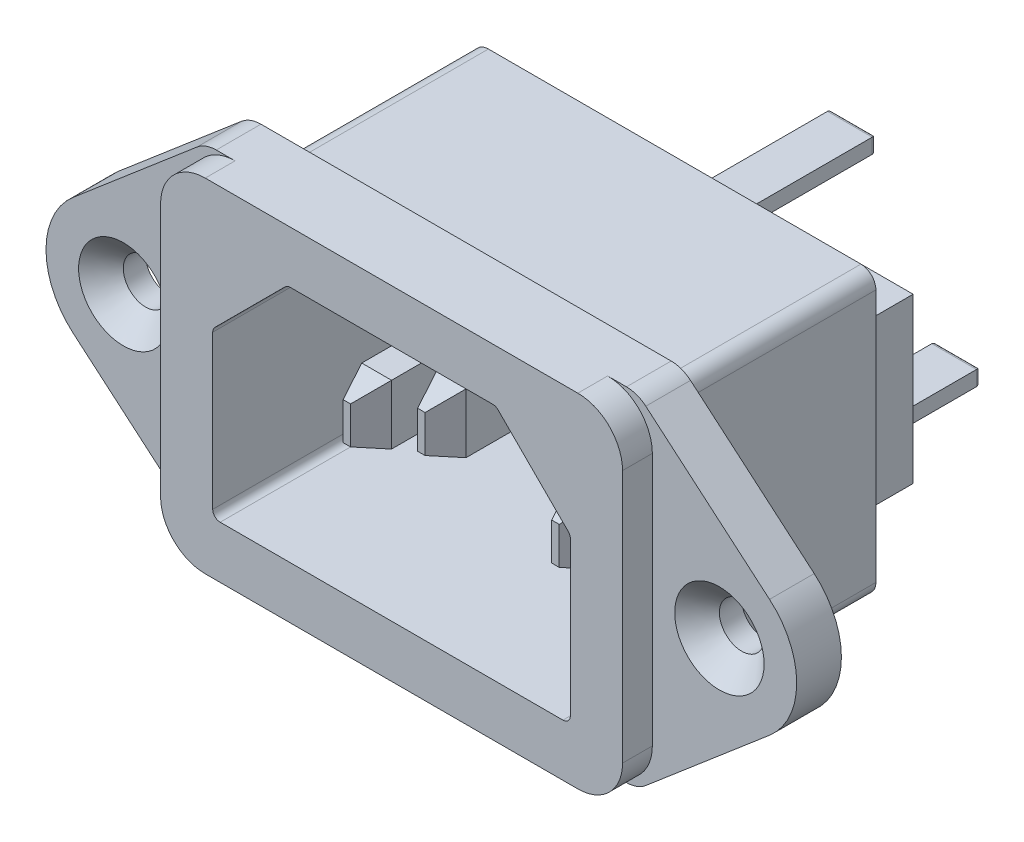
SolidWorks part; units mm, degrees
material "Gummi"
ref_plane "Ebene vorne" through (0, 0, 0) normal (0, 0, 1) x (1, 0, 0)
ref_plane "Ebene oben" through (0, 0, 0) normal (0, 1, 0) x (1, 0, 0)
ref_plane "Ebene rechts" through (0, 0, 0) normal (1, 0, 0) x (0, 0, -1)
sketch "Skizze1" plane through (0, 0, 0) normal (0, 0, 1) x (1, 0, 0)
  line L0 (28, 0) -> (-28, 0) construction
  line L1 (14.5, -11.5) -> (-14.5, -11.5)
  line L2 (14.5, -11.5) -> (14.5, 11.5) construction
  line L3 (14.5, 11.5) -> (-14.5, 11.5)
  line L4 (-14.5, -11.5) -> (-14.5, 11.5) construction
  line L5 (14.5, -11.5) -> (-14.5, 11.5) construction
  line L6 (14.5, 11.5) -> (-14.5, -11.5) construction
  line L7 (-28, 0) -> (-14.5, 11.5) construction
  line L8 (-28, 0) -> (-14.5, -11.5) construction
  line L9 (14.5, -11.5) -> (28, 0) construction
  line L10 (28, 0) -> (14.5, 11.5) construction
  line L11 (20, 0) -> (-20, 0) construction
  line L12 (-20, 0) -> (-23.3641, 3.9491) construction
  line L13 (-20, 0) -> (-23.3641, -3.9491) construction
  line L14 (20, 0) -> (23.3641, 3.9491) construction
  line L15 (20, 0) -> (23.3641, -3.9491) construction
  line L16 (-23.3641, 3.9491) -> (-14.5, 11.5)
  line L17 (-23.3641, -3.9491) -> (-14.5, -11.5)
  line L18 (23.3641, -3.9491) -> (14.5, -11.5)
  line L19 (23.3641, 3.9491) -> (14.5, 11.5)
  circle A0 centre (-20, 0) radius 1.5
  circle A1 centre (20, 0) radius 1.5
  arc A2 (-23.3641, 3.9491) -> (-23.3641, -3.9491) centre (-20, 0) ccw
  arc A3 (23.3641, 3.9491) -> (23.3641, -3.9491) centre (20, 0) cw
  point P0 (0, 0)
  point P9 (0, 0)
  point P12 (0, 0)
  dimension "D5" = 3
  dimension "D1" = 23
  dimension "D2" = 29
  dimension "D3" = 56
  dimension "D4" = 40
extrude "Aufsatz-Linear austragen1" add sketch "Skizze1" along normal blind 3 contours A3 L19 L3 L16 A2 L17 L1 L18 A1 A0
fillet "Verrundung1" radius 2 4 edges at (14.5, -11.5, 1.5) (-14.5, -11.5, 1.5) (14.5, 11.5, 1.5) (-14.5, 11.5, 1.5)
chamfer "Fase1" distance 1.5 angle 45 2 edges at (21.5, 0, 3) (-18.5, 0, 3)
sketch "Skizze2" plane through (0, 0, 3) normal (0, 0, 1) x (1, 0, 0)
  line L0 (13.7636, 11.5) -> (-13.7636, 11.5) construction
  line L1 (-12.5, -11.5) -> (12.5, -11.5)
  line L2 (-15.5, -8.5) -> (-15.5, 8.5)
  line L3 (-12.5, 11.5) -> (12.5, 11.5)
  line L4 (15.5, -8.5) -> (15.5, 8.5)
  line L5 (-15.5, -11.5) -> (15.5, 11.5) construction
  line L6 (-15.5, 11.5) -> (15.5, -11.5) construction
  arc A0 (-12.5, -11.5) -> (-15.5, -8.5) centre (-12.5, -8.5) cw
  arc A1 (12.5, -11.5) -> (15.5, -8.5) centre (12.5, -8.5) ccw
  arc A2 (12.5, 11.5) -> (15.5, 8.5) centre (12.5, 8.5) cw
  arc A3 (-15.5, 8.5) -> (-12.5, 11.5) centre (-12.5, 8.5) cw
  point P0 (0, 0)
  dimension "D2" = 3
  dimension "D1" = 31
extrude "Aufsatz-Linear austragen2" add sketch "Skizze2" along normal blind 2
sketch "Skizze4" plane through (0, 0, 0) normal (0, 0, -1) x (-1, 0, 0)
  line L1 (12.5, -9.5) -> (-12.5, -9.5)
  line L2 (13.5, -8.5) -> (13.5, 8.5)
  line L3 (12.5, 9.5) -> (-12.5, 9.5)
  line L4 (-13.5, -8.5) -> (-13.5, 8.5)
  line L5 (13.5, -9.5) -> (-13.5, 9.5) construction
  line L6 (13.5, 9.5) -> (-13.5, -9.5) construction
  arc A0 (-12.5, -9.5) -> (-13.5, -8.5) centre (-12.5, -8.5) cw
  arc A1 (12.5, -9.5) -> (13.5, -8.5) centre (12.5, -8.5) ccw
  arc A2 (13.5, 8.5) -> (12.5, 9.5) centre (12.5, 8.5) ccw
  arc A3 (-12.5, 9.5) -> (-13.5, 8.5) centre (-12.5, 8.5) ccw
  point P0 (0, 0)
  dimension "D3" = 1
  dimension "D1" = 19
  dimension "D2" = 27
extrude "Aufsatz-Linear austragen3" add sketch "Skizze4" along normal blind 14
sketch "Skizze3" plane through (0, 0, 5) normal (0, 0, 1) x (1, 0, 0)
  line L0 (-12, 3) -> (12, 3) construction
  line L1 (11.5, -8) -> (-11.5, -8)
  line L2 (12, -8) -> (12, 8) construction
  line L3 (12, 8) -> (-12, 8) construction
  line L4 (-12, -8) -> (-12, 8) construction
  line L5 (12, -8) -> (-12, 8) construction
  line L6 (12, 8) -> (-12, -8) construction
  line L7 (7, 8) -> (-7, 8) construction
  line L8 (-12, -7.5) -> (-12, 2.7929)
  line L9 (-11.8536, 3.1464) -> (-7.1464, 7.8536)
  line L10 (7.1464, 7.8536) -> (11.8536, 3.1464)
  line L11 (12, 2.7929) -> (12, -7.5)
  line L12 (6.7929, 8) -> (-6.7929, 8)
  arc A0 (11.5, -8) -> (12, -7.5) centre (11.5, -7.5) ccw
  arc A1 (12, 2.7929) -> (11.8536, 3.1464) centre (11.5, 2.7929) ccw
  arc A2 (6.7929, 8) -> (7.1464, 7.8536) centre (6.7929, 7.5) cw
  arc A3 (-6.7929, 8) -> (-7.1464, 7.8536) centre (-6.7929, 7.5) ccw
  arc A4 (-11.8536, 3.1464) -> (-12, 2.7929) centre (-11.5, 2.7929) ccw
  arc A5 (-11.5, -8) -> (-12, -7.5) centre (-11.5, -7.5) cw
  point P0 (0, 0)
  point P11 (0, 8)
  point P12 (0, 0)
  dimension "D5" = 0.5
  dimension "D1" = 24
  dimension "D2" = 16
  dimension "D3" = 11
  dimension "D4" = 14
extrude "Schnitt-Linear austragen1" cut sketch "Skizze3" against normal blind 17
sketch "Skizze5" plane through (0, 0, -14) normal (0, 0, -1) x (-1, 0, 0)
  line L1 (-12, 5.5) -> (12, 5.5)
  line L2 (-12, 5.5) -> (-12, -5.5)
  line L3 (-12, -5.5) -> (12, -5.5)
  line L4 (12, 5.5) -> (12, -5.5)
  line L5 (-12, 5.5) -> (12, -5.5) construction
  line L6 (-12, -5.5) -> (12, 5.5) construction
  point P0 (0, 0)
  dimension "D1" = 11
  dimension "D2" = 24
extrude "Aufsatz-Linear austragen4" add sketch "Skizze5" along normal blind 4
sketch "Skizze6" plane through (0, 0, -18) normal (0, 0, -1) x (-1, 0, 0)
  line L0 (0, 0) -> (0, 50000) construction
  line L1 (-7, -5) -> (7, -5) construction
  line L2 (12, 5.5) -> (-12, 5.5) construction
  line L3 (1.5, 4.5) -> (-1.5, 4.5)
  line L4 (1.5, 4.5) -> (1.5, 5.5)
  line L5 (1.5, 5.5) -> (-1.5, 5.5)
  line L6 (-1.5, 4.5) -> (-1.5, 5.5)
  line L7 (1.5, 4.5) -> (-1.5, 5.5) construction
  line L8 (1.5, 5.5) -> (-1.5, 4.5) construction
  line L9 (-12, -5.5) -> (12, -5.5) construction
  line L10 (-8.5, -4.5) -> (-5.5, -4.5)
  line L11 (-8.5, -4.5) -> (-8.5, -5.5)
  line L12 (-8.5, -5.5) -> (-5.5, -5.5)
  line L13 (-5.5, -4.5) -> (-5.5, -5.5)
  line L14 (-8.5, -4.5) -> (-5.5, -5.5) construction
  line L15 (-8.5, -5.5) -> (-5.5, -4.5) construction
  line L16 (-12, -5.5) -> (12, -5.5) construction
  line L17 (8.5, -4.5) -> (5.5, -4.5)
  line L18 (8.5, -4.5) -> (8.5, -5.5)
  line L19 (8.5, -5.5) -> (5.5, -5.5)
  line L20 (5.5, -4.5) -> (5.5, -5.5)
  line L21 (8.5, -4.5) -> (5.5, -5.5) construction
  line L22 (8.5, -5.5) -> (5.5, -4.5) construction
  point P3 (0, 5)
  point P6 (0, -5)
  dimension "D1" = 3
  dimension "D2" = 1
  dimension "D3" = 3
  dimension "D4" = 1
  dimension "D5" = 11
extrude "Aufsatz-Linear austragen5" add sketch "Skizze6" along normal blind 8
sketch "Skizze7" plane through (0, 0, -12) normal (0, 0, 1) x (1, 0, 0)
  line L0 (0, 0) -> (0, 50000) construction
  line L3 (-7, -2) -> (7, -2) construction
  line L4 (-11.5, -8) -> (11.5, -8) construction
  line L5 (-6, -4) -> (-8, -4)
  line L6 (-6, -4) -> (-6, 0)
  line L7 (-6, 0) -> (-8, 0)
  line L8 (-8, -4) -> (-8, 0)
  line L9 (-6, -4) -> (-8, 0) construction
  line L10 (-6, 0) -> (-8, -4) construction
  line L11 (6, -4) -> (8, -4)
  line L12 (6, -4) -> (6, 0)
  line L13 (6, 0) -> (8, 0)
  line L14 (8, -4) -> (8, 0)
  line L15 (6, -4) -> (8, 0) construction
  line L16 (6, 0) -> (8, -4) construction
  point P5 (0, -2)
  dimension "D1" = 2
  dimension "D2" = 4
  dimension "D3" = 14
  dimension "D4" = 4
extrude "Aufsatz-Linear austragen6" add sketch "Skizze7" along normal blind 13
sketch "Skizze8" plane through (0, 0, -12) normal (0, 0, 1) x (1, 0, 0)
  line L0 (0, 0) -> (0, 50000) construction
  line L1 (6.7929, 8) -> (-6.7929, 8) construction
  line L2 (-1, 4) -> (1, 4)
  line L3 (-1, 4) -> (-1, 0)
  line L4 (-1, 0) -> (1, 0)
  line L5 (1, 4) -> (1, 0)
  line L6 (-1, 4) -> (1, 0) construction
  line L7 (-1, 0) -> (1, 4) construction
  point P3 (0, 2)
  dimension "D1" = 2
  dimension "D2" = 4
  dimension "D3" = 4
extrude "Aufsatz-Linear austragen7" add sketch "Skizze8" along normal blind 15
chamfer "Fase2" distance 2 distance2 0.75 12 edges at (7, -4, 1) (6, -2, 1) (7, 0, 1) (8, -2, 1) (0, 0, 3) (-1, 2, 3) (0, 4, 3) (1, 2, 3) (-7, 0, 1) (-6, -2, 1) (-7, -4, 1) (-8, -2, 1)
fillet "Verrundung2" radius 0.25 12 edges at (-7, -4.5, -26) (-8.5, -5, -26) (-7, -5.5, -26) (-5.5, -5, -26) (7, -5.5, -26) (8.5, -5, -26) (7, -4.5, -26) (5.5, -5, -26) (0, 5.5, -26) (-1.5, 5, -26) (0, 4.5, -26) (1.5, 5, -26)
